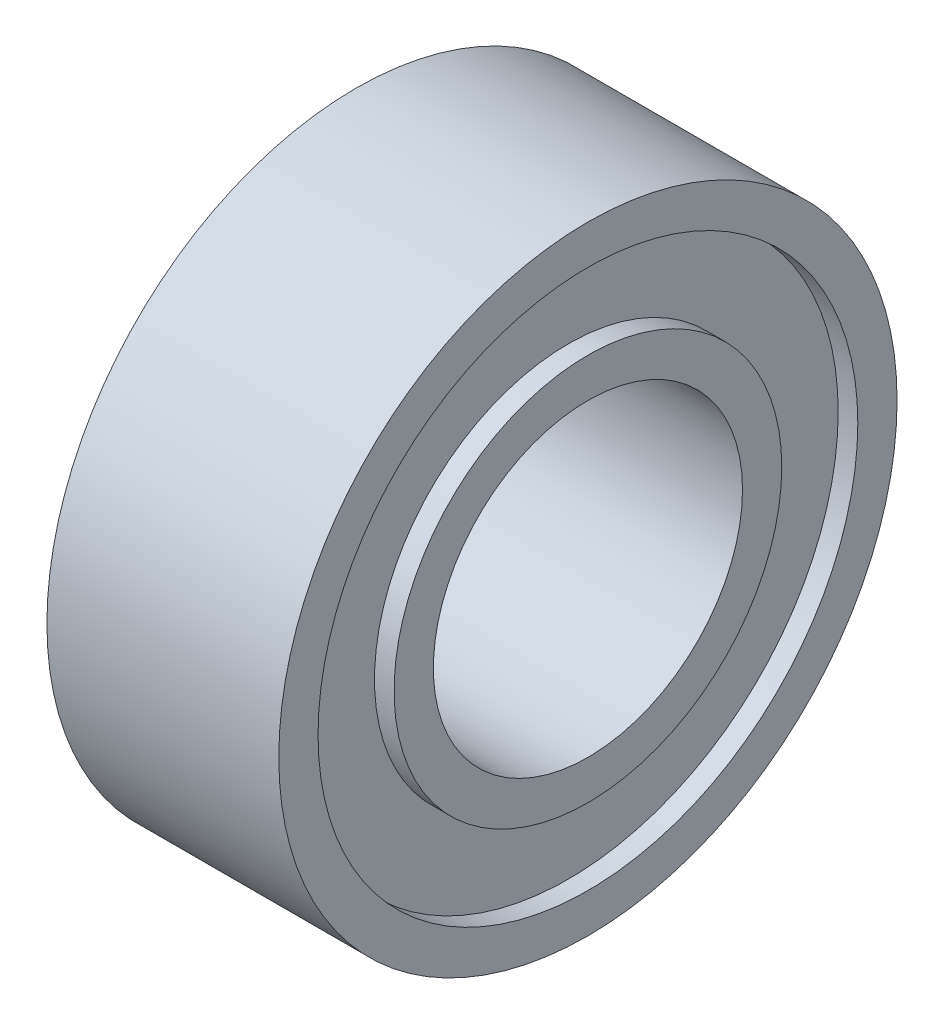
SolidWorks part; units mm, degrees
material "AISI 304"
ref_plane "Front Plane" through (0, 0, 0) normal (0, 0, 1) x (1, 0, 0)
ref_plane "Top Plane" through (0, 0, 0) normal (0, 1, 0) x (1, 0, 0)
ref_plane "Right Plane" through (0, 0, 0) normal (1, 0, 0) x (0, 0, -1)
sketch "Sketch1" plane through (0, 0, 0) normal (1, 0, 0) x (0, 0, -1)
  circle A0 centre (0, 0) radius 2
  circle A1 centre (0, 0) radius 4
  dimension "D1" = 8
  dimension "D2" = 4
extrude "Boss-Extrude1" add sketch "Sketch1" along normal mid plane 3
sketch "Sketch2" plane through (1.5, 0, 0) normal (1, 0, 0) x (0, 0, -1)
  circle A0 centre (0, 0) radius 2.508
  circle A1 centre (0, 0) radius 3.492
  circle A2 centre (0, 0) radius 4 construction
  circle A3 centre (0, 0) radius 2 construction
  dimension "D1" = 0.508
  dimension "D2" = 0.508
extrude "Cut-Extrude1" cut sketch "Sketch2" against normal blind 0.254
mirror "Mirror1" about plane through (0, 0, 0) normal (1, 0, 0) of "Cut-Extrude1"
